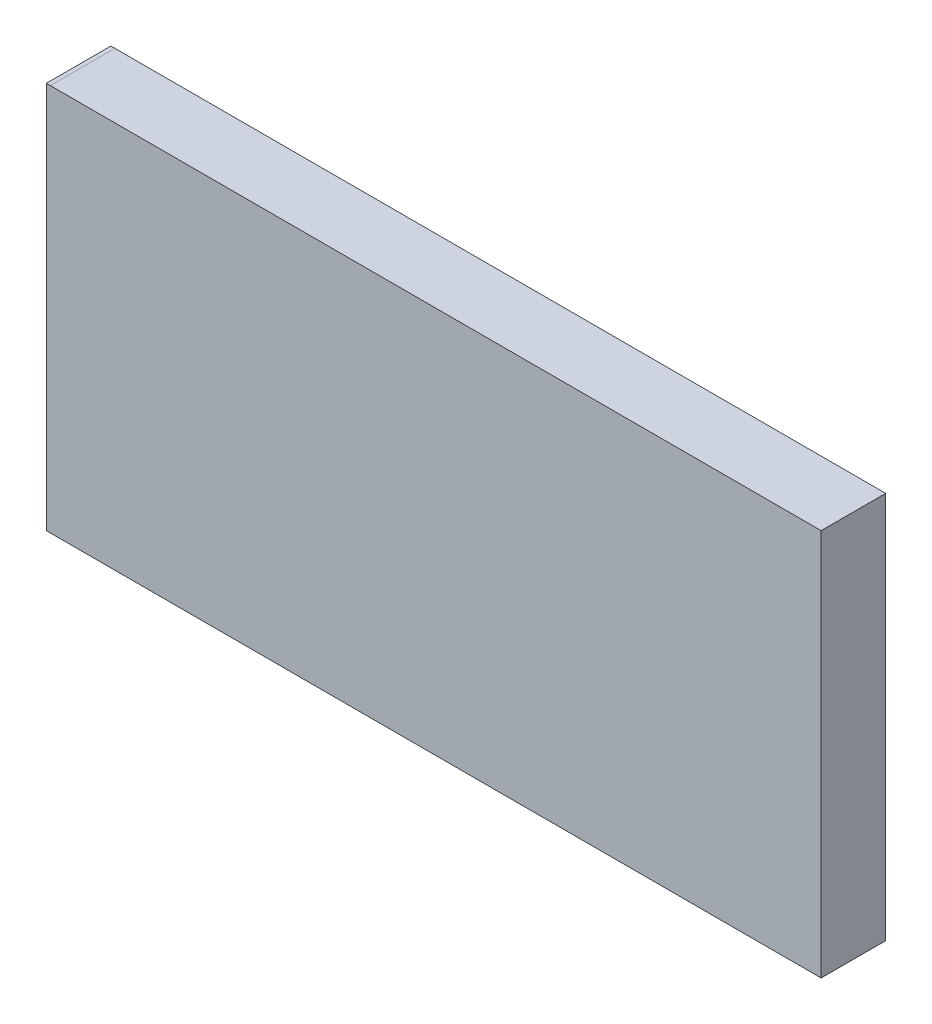
SolidWorks part; units mm, degrees
ref_plane "Front Plane" through (0, 0, 0) normal (0, 0, 1) x (1, 0, 0)
ref_plane "Top Plane" through (0, 0, 0) normal (0, 1, 0) x (1, 0, 0)
ref_plane "Right Plane" through (0, 0, 0) normal (1, 0, 0) x (0, 0, -1)
sketch "Sketch1" plane through (0, 0, 0) normal (0, 0, 1) x (1, 0, 0)
  line L1 (0, 0) -> (152.4, 0)
  line L2 (0, 0) -> (0, -76.2)
  line L3 (0, -76.2) -> (152.4, -76.2)
  line L4 (152.4, 0) -> (152.4, -76.2)
  dimension "D1" = 152.4
  dimension "D2" = 76.2
extrude "Boss-Extrude1" add sketch "Sketch1" along normal blind 12.7
sketch "Sketch2" plane through (0, -76.2, 0) normal (0, -1, 0) x (1, 0, 0)
  line L0 (41.91, 0) -> (-41.91, 0) construction
  line L1 (152.4, 12.7) -> (151.2775, 12.7)
  line L2 (152.4, 12.7) -> (152.4, 0)
  line L3 (152.4, 0) -> (151.2775, 0)
  line L4 (151.2775, 12.7) -> (151.2775, 0)
split line "Split Line1"
sketch "Sketch3" plane through (0, 0, 0) normal (0, 1, 0) x (1, 0, 0)
  line L1 (0, 0) -> (0.8022, 0)
  line L2 (0, 0) -> (0, -12.7041)
  line L3 (0, -12.7041) -> (0.8022, -12.7041)
  line L4 (0.8022, 0) -> (0.8022, -12.7041)
split line "Split Line2"
